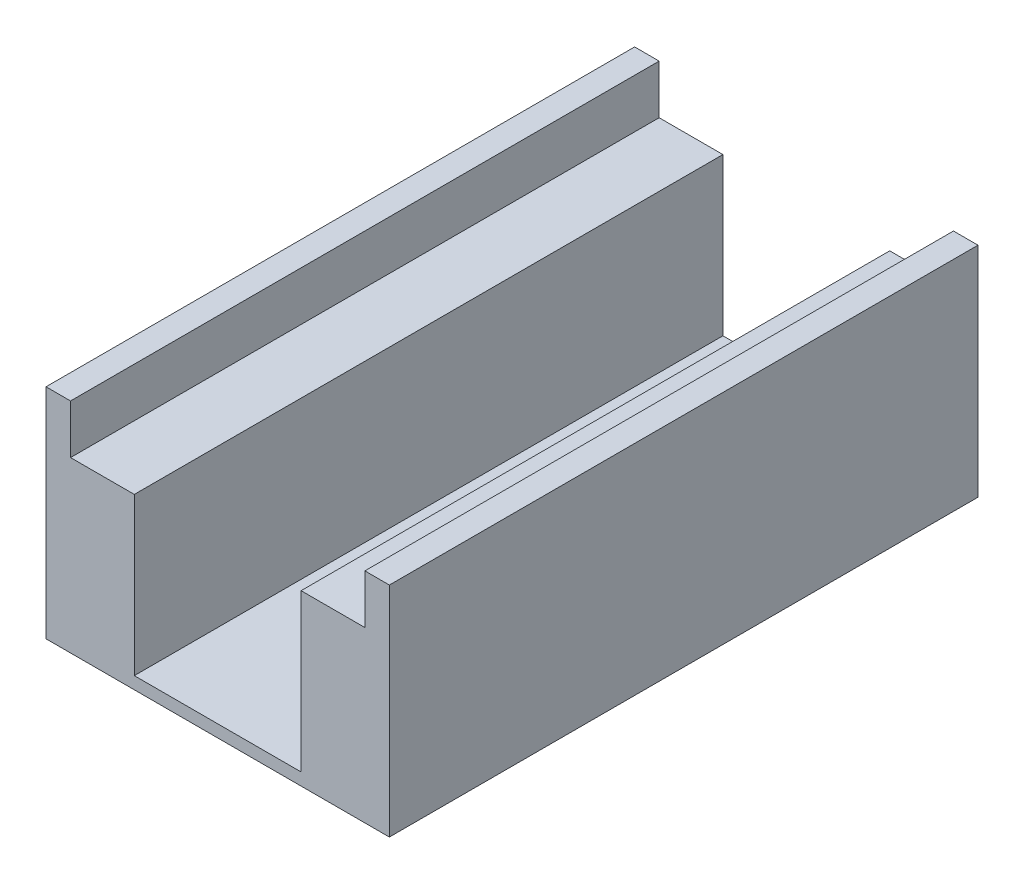
SolidWorks part; units mm, degrees
ref_plane "Front Plane" through (0, 0, 0) normal (0, 0, 1) x (1, 0, 0)
ref_plane "Top Plane" through (0, 0, 0) normal (0, 1, 0) x (1, 0, 0)
ref_plane "Right Plane" through (0, 0, 0) normal (1, 0, 0) x (0, 0, -1)
sketch "Sketch1" plane through (0, 0, 0) normal (0, 1, 0) x (1, 0, 0)
  line L1 (-44.45, 76.2) -> (44.45, 76.2)
  line L2 (-44.45, 76.2) -> (-44.45, -76.2)
  line L3 (-44.45, -76.2) -> (44.45, -76.2)
  line L4 (44.45, 76.2) -> (44.45, -76.2)
  line L5 (-44.45, 76.2) -> (44.45, -76.2) construction
  line L6 (-44.45, -76.2) -> (44.45, 76.2) construction
  point P0 (0, 0)
  dimension "D1" = 88.9
  dimension "D2" = 152.4
extrude "Boss-Extrude1" add sketch "Sketch1" along normal blind 3.175
sketch "Sketch2" plane through (0, 3.175, 0) normal (0, 1, 0) x (1, 0, 0)
  line L0 (-44.45, -76.2) -> (44.45, -76.2) construction
  line L1 (-44.45, 76.2) -> (-21.59, 76.2)
  line L2 (-44.45, 76.2) -> (-44.45, -76.2)
  line L3 (-44.45, -76.2) -> (-21.59, -76.2)
  line L4 (-21.59, 76.2) -> (-21.59, -76.2)
  line L6 (44.45, 76.2) -> (21.59, 76.2)
  line L7 (44.45, 76.2) -> (44.45, -76.2)
  line L8 (44.45, -76.2) -> (21.59, -76.2)
  line L9 (21.59, 76.2) -> (21.59, -76.2)
  dimension "D1" = 43.18
extrude "Boss-Extrude2" add sketch "Sketch2" along normal blind 40.64
sketch "Sketch3" plane through (0, 43.815, 0) normal (0, 1, 0) x (1, 0, 0)
  line L1 (-44.45, 76.2) -> (-38.1, 76.2)
  line L2 (-44.45, 76.2) -> (-44.45, -76.2)
  line L3 (-44.45, -76.2) -> (-38.1, -76.2)
  line L4 (-38.1, 76.2) -> (-38.1, -76.2)
  line L5 (21.59, -76.2) -> (44.45, -76.2) construction
  line L6 (44.45, 76.2) -> (38.1, 76.2)
  line L7 (44.45, 76.2) -> (44.45, -76.2)
  line L8 (44.45, -76.2) -> (38.1, -76.2)
  line L9 (38.1, 76.2) -> (38.1, -76.2)
  line L10 (-44.45, -76.2) -> (-21.59, -76.2) construction
  point P5 (-26.5997, -76.2)
  point P14 (0, 0)
  dimension "D1" = 6.35
extrude "Boss-Extrude3" add sketch "Sketch3" along normal blind 12.7
